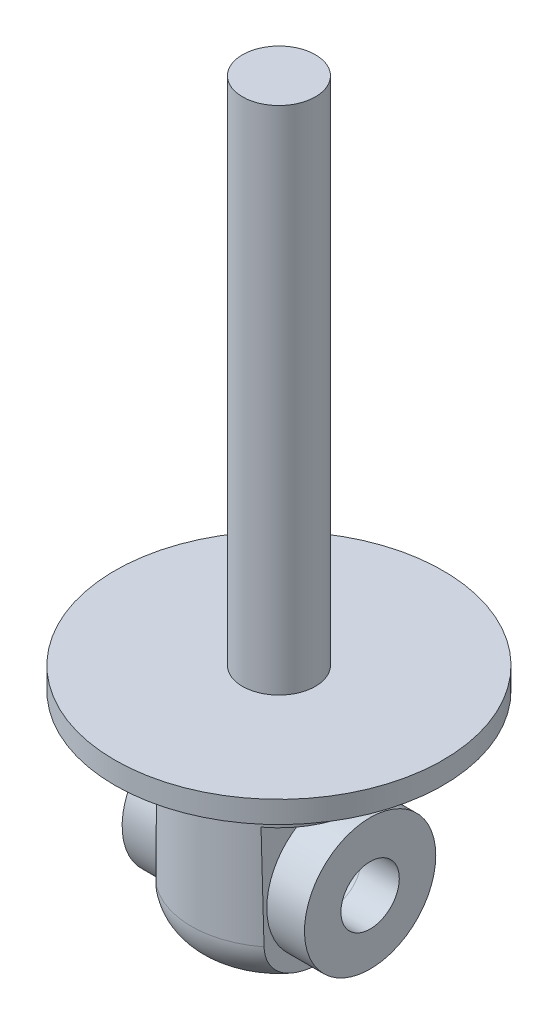
SolidWorks part; units mm, degrees
ref_plane "Front Plane" through (0, 0, 0) normal (0, 0, 1) x (1, 0, 0)
ref_plane "Top Plane" through (0, 0, 0) normal (0, 1, 0) x (1, 0, 0)
ref_plane "Right Plane" through (0, 0, 0) normal (1, 0, 0) x (0, 0, -1)
sketch "Sketch1" plane through (0, 0, 0) normal (0, 1, 0) x (1, 0, 0)
  circle A0 centre (0, 0) radius 22.5
  dimension "D1" = 45
extrude "Boss-Extrude1" add sketch "Sketch1" along normal blind 3
sketch "Sketch2" plane through (0, 3, 0) normal (0, 1, 0) x (1, 0, 0)
  circle A0 centre (0, 0) radius 5
  dimension "D1" = 10
extrude "Boss-Extrude2" add sketch "Sketch2" along normal blind 70
sketch "Sketch3" plane through (0, 0, 0) normal (0, -1, 0) x (1, 0, 0)
  circle A0 centre (0, 0) radius 12
  dimension "D1" = 24
extrude "Boss-Extrude3" add sketch "Sketch3" along normal blind 28
fillet "Fillet1" radius 6 1 edges at (0, -28, -12)
sketch "Sketch4" plane through (0, 0, 0) normal (0, 0, 1) x (1, 0, 0)
  line L0 (0, 0) -> (0, -28) construction
  line L1 (-6, -28) -> (6, -28) construction
  line L2 (7.5, -27.8095) -> (29.5892, -27.8095)
  line L3 (29.5892, -27.8095) -> (29.5892, -7.8095)
  line L4 (29.5892, -7.8095) -> (7.1682, -7.8095)
  line L5 (7.1682, -7.8095) -> (7.5, -27.8095)
  line L6 (-7.1682, -7.8095) -> (-7.5, -27.8095)
  line L7 (-29.5892, -7.8095) -> (-7.1682, -7.8095)
  line L8 (-29.5892, -27.8095) -> (-29.5892, -7.8095)
  line L9 (-7.5, -27.8095) -> (-29.5892, -27.8095)
  arc A0 (6, -28) -> (12, -22) centre (6, -22) ccw construction
  point P16 (0, 0)
  point P17 (0, 0)
  dimension "D1" = 15
  dimension "D2" = 20
  dimension "D3" = 22.0892
extrude "Cut-Extrude1" cut sketch "Sketch4" against normal through all both and the other way through all
sketch "Sketch5" plane through (-7.0367, 0.1167, 0) normal (-0.9999, 0.0166, 0) x (0, 0, 1)
  line L0 (0, -0.3732) -> (0, -27.93) construction
  circle A0 centre (0, -17.93) radius 4
  ellipse E0 centre (0, 0) end of major axis (22.5, 0) minor radius 0.3732 construction
  spline S0 degree 3 poles (-9.4439, -22.1198) (-9.437, -22.6437) (-9.3451, -23.1513) (-9.0858, -23.8896) (-8.9797, -24.1286) (-8.7346, -24.5838) (-8.5952, -24.8015) (-8.2837, -25.2182) (-8.1117, -25.4164) (-7.7466, -25.784) (-7.5524, -25.9549) (-7.1425, -26.2731) (-6.9256, -26.4208) (-6.4814, -26.6881) (-6.2534, -26.8085) (-5.5536, -27.135) (-5.0643, -27.3069) (-4.0611, -27.5768) (-3.556, -27.6729) (-2.5414, -27.8144) (-2.0319, -27.8597) (-1.0099, -27.9176) (-0.4975, -27.9303) (0.5296, -27.9298) (1.0456, -27.9164) (2.0728, -27.8565) (2.5841, -27.8098) (3.5994, -27.6653) (4.1035, -27.5674) (5.1009, -27.2949) (5.5875, -27.1215) (6.2835, -26.7931) (6.5102, -26.6721) (6.9518, -26.4035) (7.1666, -26.2557) (7.5718, -25.9384) (7.7637, -25.768) (8.1244, -25.4022) (8.294, -25.2056) (8.7583, -24.5808) (9.001, -24.1307) (9.2574, -23.4014) (9.3245, -23.1477) (9.4156, -22.6382) (9.4405, -22.3805) (9.4439, -22.1198) knots 0 0 0 0 0.0625 0.0625 0.09375 0.09375 0.125 0.125 0.15625 0.15625 0.1875 0.1875 0.21875 0.21875 0.25 0.25 0.3125 0.3125 0.375 0.375 0.4375 0.4375 0.5 0.5 0.5625 0.5625 0.625 0.625 0.6875 0.6875 0.75 0.75 0.78125 0.78125 0.8125 0.8125 0.84375 0.84375 0.875 0.875 0.9375 0.9375 0.96875 0.96875 1 1 1 1 construction
  dimension "D1" = 8
  dimension "D2" = 10
extrude "Cut-Extrude4" cut sketch "Sketch5" against normal through all
sketch "Sketch13" plane through (0, 0, 0) normal (1, 0, 0) x (0, 0, -1)
  circle A0 centre (0, -17.8208) radius 9
  ellipse E0 centre (0, -18.0542) end of major axis (0, -14.0526) minor radius 4 construction
  ellipse E1 centre (0, -18.0542) end of major axis (0, -14.0526) minor radius 4
  point P2 (0, 0)
  dimension "D1" = 18
extrude "Boss-Extrude6" add sketch "Sketch13" along normal mid plane 25
